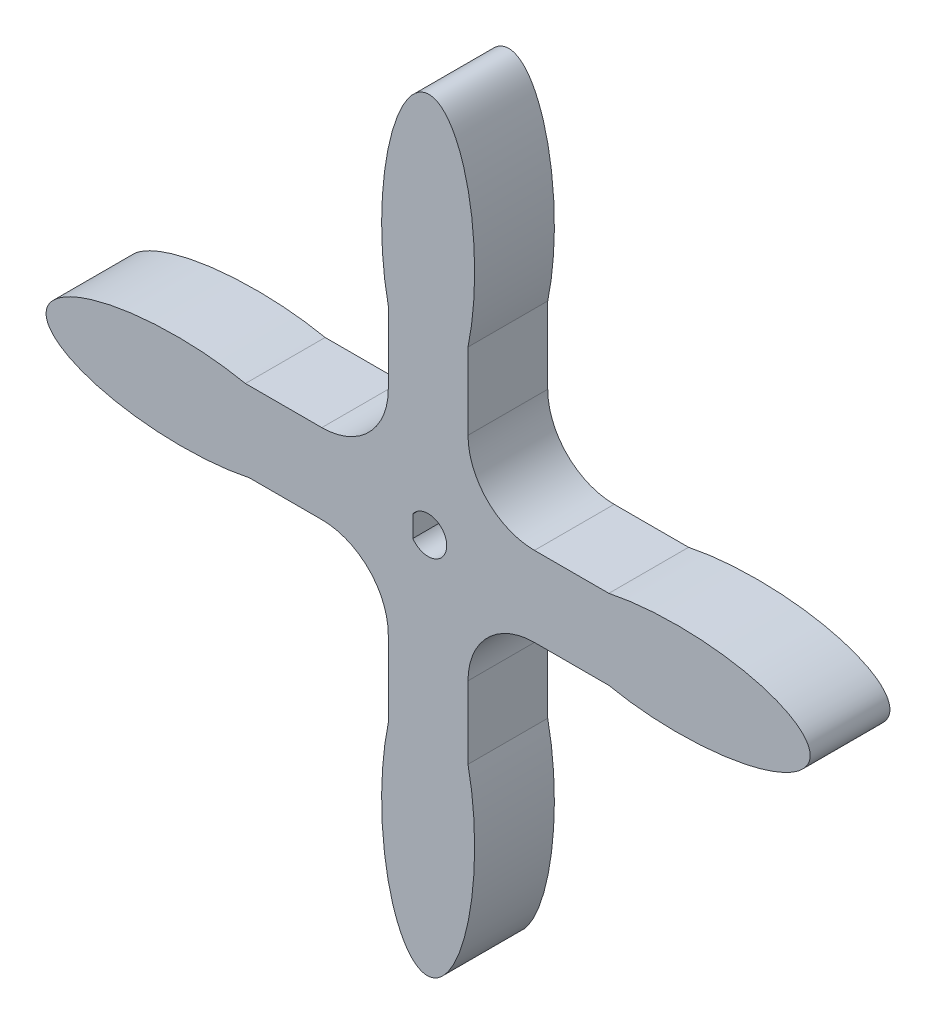
SolidWorks part; units mm, degrees
material "POM 乙缩醛共聚物"
ref_plane "前视基准面" through (0, 0, 0) normal (0, 0, 1) x (1, 0, 0)
ref_plane "上视基准面" through (0, 0, 0) normal (0, 1, 0) x (1, 0, 0)
ref_plane "右视基准面" through (0, 0, 0) normal (1, 0, 0) x (0, 0, -1)
sketch "草图2" plane through (0, 0, 0) normal (0, 0, 1) x (1, 0, 0)
  line L1 (-47.5, 6) -> (47.5, 6)
  line L2 (-47.5, 6) -> (-47.5, -6)
  line L3 (-47.5, -6) -> (47.5, -6)
  line L4 (47.5, 6) -> (47.5, -6)
  line L5 (-47.5, 6) -> (47.5, -6) construction
  line L6 (-47.5, -6) -> (47.5, 6) construction
  point P0 (0, 0)
  dimension "D1" = 95
  dimension "D2" = 12
extrude "凸台-拉伸2" add sketch "草图2" along normal blind 12
sketch "草图7" plane through (0, 0, 12) normal (0, 0, 1) x (1, 0, 0)
  line L1 (-6, 47.5) -> (6, 47.5)
  line L2 (-6, 47.5) -> (-6, -47.5)
  line L3 (-6, -47.5) -> (6, -47.5)
  line L4 (6, 47.5) -> (6, -47.5)
  line L5 (-6, 47.5) -> (6, -47.5) construction
  line L6 (-6, -47.5) -> (6, 47.5) construction
  point P0 (0, 0)
  dimension "D1" = 95
  dimension "D2" = 12
extrude "凸台-拉伸6" add sketch "草图7" against normal up to surface (12 mm away) up to face at (0, 0, 0)
sketch "草图5" plane through (0, 0, 0) normal (0, 0, -1) x (-1, 0, 0)
  line L0 (0, 0) -> (-37.5, 0) construction
  line L1 (0, 6) -> (0, 0) construction
  line L2 (-57.5, 0) -> (-37.5, 0) construction
  ellipse E0 centre (-37.5, 0) end of major axis (-17.5, 0) minor radius 7
  ellipse E1 centre (0, 37.5) end of major axis (-0.1423, 57.4995) minor radius 7.0002
  ellipse E2 centre (37.5, 0) end of major axis (57.4995, 0.1423) minor radius 7.0002
  ellipse E3 centre (0, -37.5) end of major axis (0.1423, -57.4995) minor radius 7.0002
  point P31 (0, 0)
  dimension "D1" = 7
  dimension "D2" = 37.5
  dimension "D3" = 20
  dimension "D4" = 37.5
  dimension "D5" = 37.5
  dimension "D6" = 37.5
extrude "凸台-拉伸5" add sketch "草图5" against normal up to surface (12 mm away) up to face at (0, 0, 12)
sketch "草图8" plane through (0, 0, 12) normal (0, 0, 1) x (1, 0, 0)
  line L0 (-2.3, 1.5969) -> (-2.3, -1.5969)
  circle A0 centre (0, 0) radius 2.8
  dimension "D1" = 5.6
  dimension "D2" = 2.3
extrude "切除-拉伸1" cut sketch "草图8" against normal blind 10.5 contours L0 A0
fillet "圆角1" radius 10 4 edges at (6, 6, 6) (-6, 6, 6) (-6, -6, 6) (6, -6, 6)
sketch "草图9" plane through (0, 0, 1.5) normal (0, 0, 1) x (1, 0, 0)
  circle A0 centre (0, 0) radius 1.5
  dimension "D1" = 3
extrude "切除-拉伸2" cut sketch "草图9" against normal through all
